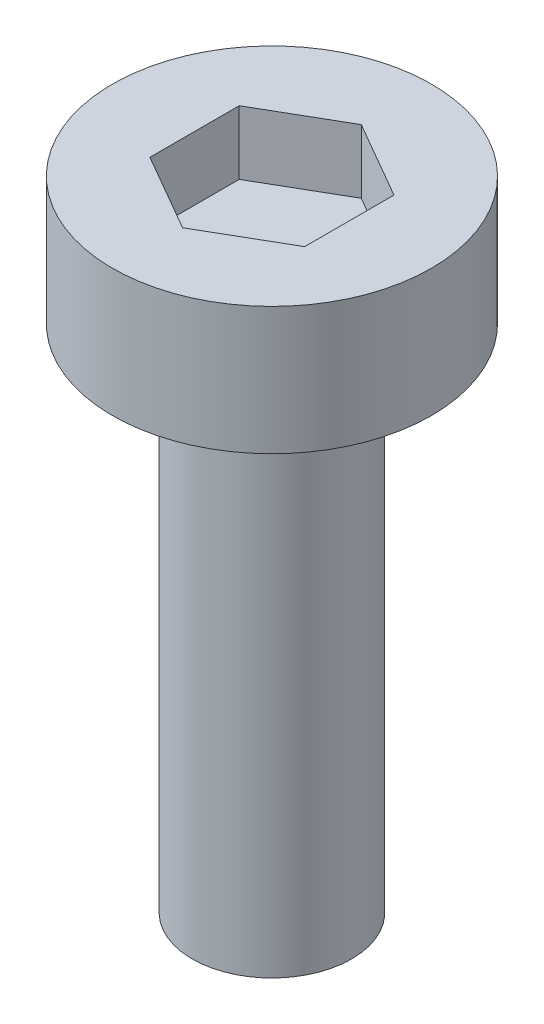
SolidWorks part; units mm, degrees
ref_plane "Front Plane" through (0, 0, 0) normal (0, 0, 1) x (1, 0, 0)
ref_plane "Top Plane" through (0, 0, 0) normal (0, 1, 0) x (1, 0, 0)
ref_plane "Right Plane" through (0, 0, 0) normal (1, 0, 0) x (0, 0, -1)
sketch "Sketch1" plane through (0, 0, 0) normal (0, 0, 1) x (1, 0, 0)
  line L0 (0, 0) -> (0, 20)
  line L1 (0, 20) -> (5, 20)
  line L2 (5, 20) -> (5, 16)
  line L4 (5, 16) -> (2.5, 16)
  line L5 (2.5, 16) -> (2.5, 0)
  line L6 (2.5, 0) -> (0, 0)
  dimension "D1" = 2.5
  dimension "D2" = 5
  dimension "D3" = 4
  dimension "D4" = 16
revolve "Revolve1" add sketch "Sketch1" angle 360 about L0
sketch "Sketch2" plane through (0, 20, 0) normal (0, 1, 0) x (1, 0, 0)
  line L1 (0, -2.8001) -> (2.425, -1.4001)
  line L2 (2.425, -1.4001) -> (2.425, 1.4001)
  line L3 (2.425, 1.4001) -> (0, 2.8001)
  line L4 (0, 2.8001) -> (-2.425, 1.4001)
  line L5 (-2.425, 1.4001) -> (-2.425, -1.4001)
  line L6 (-2.425, -1.4001) -> (0, -2.8001)
  circle A0 centre (0, 0) radius 2.425 construction
  dimension "D1" = 4.85
extrude "Cut-Extrude1" cut sketch "Sketch2" against normal blind 2
